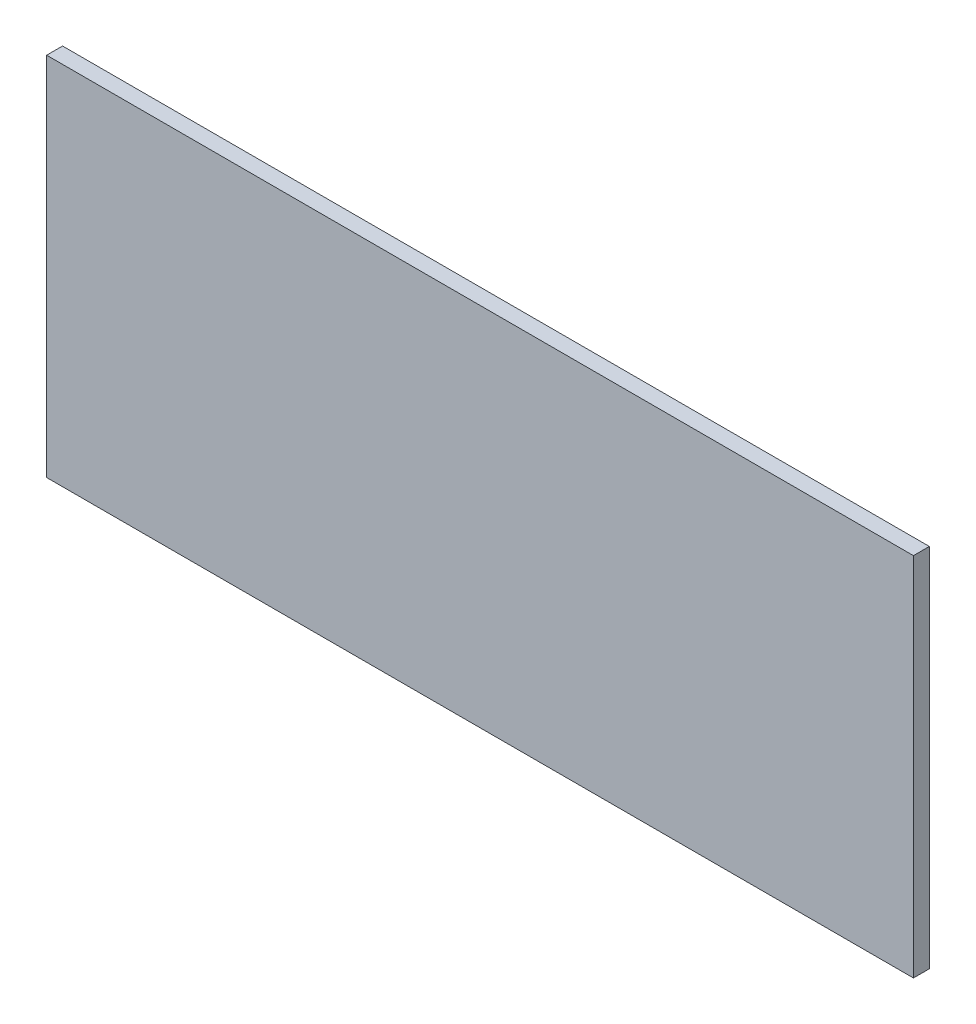
SolidWorks part; units mm, degrees
ref_plane "前视基准面" through (0, 0, 0) normal (0, 0, 1) x (1, 0, 0)
ref_plane "上视基准面" through (0, 0, 0) normal (0, 1, 0) x (1, 0, 0)
ref_plane "右视基准面" through (0, 0, 0) normal (1, 0, 0) x (0, 0, -1)
sketch "草图1" plane through (0, 0, 0) normal (0, 0, 1) x (1, 0, 0)
  line L1 (-272.5, 115) -> (272.5, 115)
  line L2 (-272.5, 115) -> (-272.5, -115)
  line L3 (-272.5, -115) -> (272.5, -115)
  line L4 (272.5, 115) -> (272.5, -115)
  line L5 (-272.5, 115) -> (272.5, -115) construction
  line L6 (-272.5, -115) -> (272.5, 115) construction
  point P0 (0, 0)
  dimension "D1" = 545
  dimension "D2" = 230
extrude "凸台-拉伸1" add sketch "草图1" along normal blind 10
